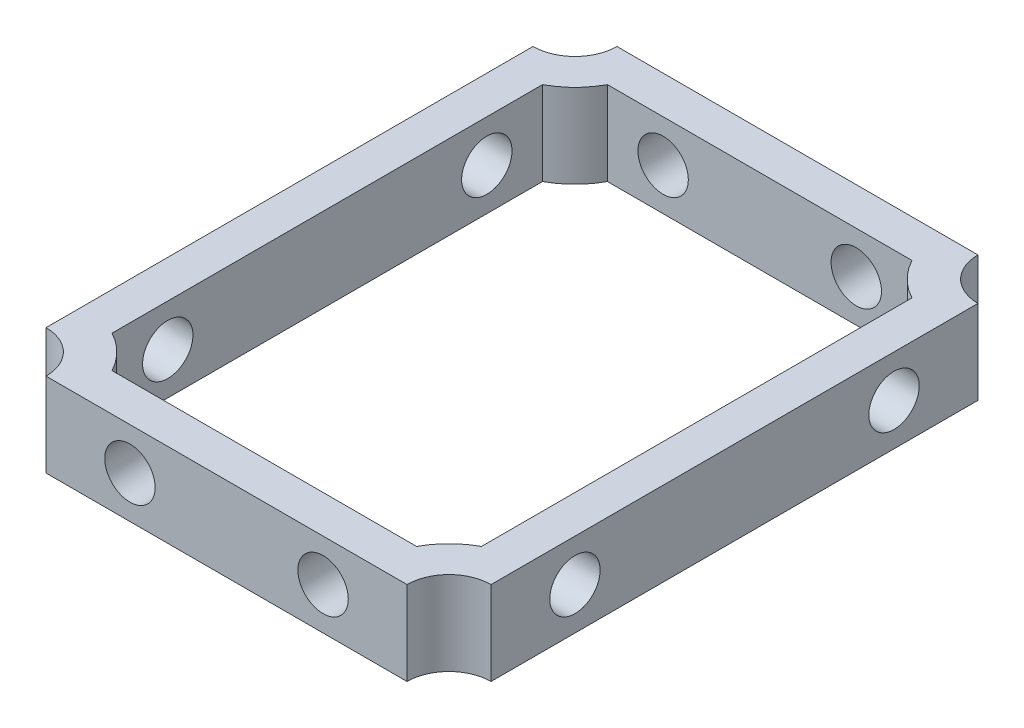
SolidWorks part; units mm, degrees
ref_plane "Front Plane" through (0, 0, 0) normal (0, 0, 1) x (1, 0, 0)
ref_plane "Top Plane" through (0, 0, 0) normal (0, 1, 0) x (1, 0, 0)
ref_plane "Right Plane" through (0, 0, 0) normal (1, 0, 0) x (0, 0, -1)
sketch "Sketch1" plane through (0, 0, 0) normal (0, 1, 0) x (1, 0, 0)
  line L0 (0, -50.2671) -> (0, 37.7922) construction
  line L1 (-21.5, 34) -> (21.5, 34)
  line L2 (-26.5, 29) -> (-26.5, -29)
  line L3 (-21.5, -34) -> (21.5, -34)
  line L4 (26.5, 29) -> (26.5, -29)
  line L5 (-26.5, 34) -> (26.5, -34) construction
  line L6 (-26.5, -34) -> (26.5, 34) construction
  line L7 (-59.6001, 0) -> (76.6347, 0) construction
  line L8 (-22, 25.6334) -> (-22, -25.6334)
  line L9 (-18.1334, -29.5) -> (18.1334, -29.5)
  line L10 (22, 25.6334) -> (22, -25.6334)
  line L11 (-18.1334, 29.5) -> (18.1334, 29.5)
  arc A0 (-21.5, -34) -> (-26.5, -29) centre (-26.5, -34) ccw
  arc A1 (26.5, -29) -> (21.5, -34) centre (26.5, -34) ccw
  arc A2 (21.5, 34) -> (26.5, 29) centre (26.5, 34) ccw
  arc A3 (-26.5, 29) -> (-21.5, 34) centre (-26.5, 34) ccw
  arc A4 (-18.1334, -29.5) -> (-22, -25.6334) centre (-26.5, -34) ccw
  arc A5 (22, -25.6334) -> (18.1334, -29.5) centre (26.5, -34) ccw
  arc A6 (18.1334, 29.5) -> (22, 25.6334) centre (26.5, 34) ccw
  arc A7 (-22, 25.6334) -> (-18.1334, 29.5) centre (-26.5, 34) ccw
  point P0 (0, 0)
  dimension "D3" = 10
  dimension "D1" = 4.5
  dimension "D5" = 53
  dimension "D6" = 34
extrude "Boss-Extrude1" add sketch "Sketch1" along normal blind 10
sketch "Sketch2" plane through (26.5, 0, 0) normal (1, 0, 0) x (0, 0, -1)
  line L0 (-29, 10) -> (-29, 0) construction
  line L1 (-29, 10) -> (29, 10) construction
  line L2 (29, 10) -> (29, 0) construction
  circle A0 centre (-19, 5) radius 3
  circle A1 centre (19, 5) radius 3
  dimension "D2" = 6
  dimension "D1" = 10
  dimension "D3" = 5
  dimension "D4" = 10
extrude "Cut-Extrude1" cut sketch "Sketch2" against normal through all
sketch "Sketch3" plane through (0, 0, 34) normal (0, 0, 1) x (1, 0, 0)
  line L0 (-21.5, 10) -> (21.5, 10) construction
  line L1 (21.5, 10) -> (21.5, 0) construction
  line L2 (-21.5, 10) -> (-21.5, 0) construction
  circle A0 centre (11.5, 5) radius 3
  circle A1 centre (-11.5, 5) radius 3
  dimension "D1" = 6
  dimension "D4" = 10
  dimension "D2" = 5
  dimension "D3" = 10
extrude "Cut-Extrude2" cut sketch "Sketch3" against normal through all
